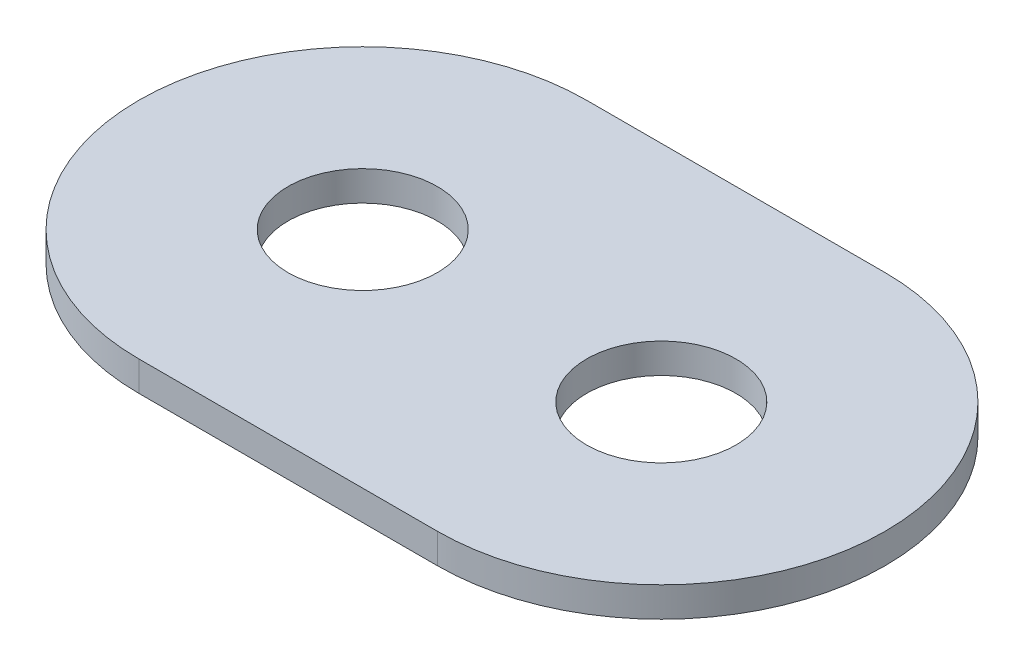
SolidWorks part; units mm, degrees
ref_plane "Front Plane" through (0, 0, 0) normal (0, 0, 1) x (1, 0, 0)
ref_plane "Top Plane" through (0, 0, 0) normal (0, 1, 0) x (1, 0, 0)
ref_plane "Right Plane" through (0, 0, 0) normal (1, 0, 0) x (0, 0, -1)
sketch "Sketch1" plane through (0, 0, 0) normal (0, 1, 0) x (1, 0, 0)
  line L0 (-10, 0) -> (10, 0) construction
  line L1 (-10, 15) -> (10, 15)
  line L2 (-10, -15) -> (10, -15)
  arc A0 (-10, 15) -> (-10, -15) centre (-10, 0) ccw
  arc A1 (10, -15) -> (10, 15) centre (10, 0) ccw
  circle A2 centre (10, 0) radius 5
  circle A3 centre (-10, 0) radius 5
  circle A4 centre (-10, 0) radius 2.5
  circle A5 centre (10, 0) radius 2.5
  point P2 (0, 0)
  dimension "D1" = 30
  dimension "D3" = 10
  dimension "D4" = 10
  dimension "D5" = 5
  dimension "D6" = 5
  dimension "D2" = 20
extrude "Boss-Extrude1" add sketch "Sketch1" along normal blind 2
